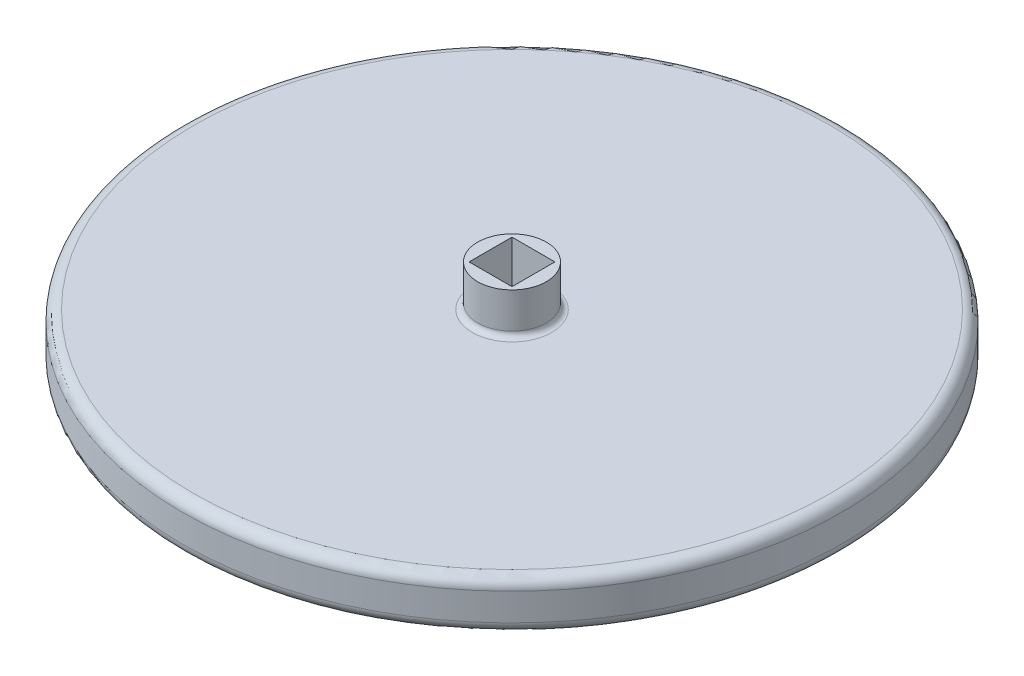
SolidWorks part; units mm, degrees
ref_plane "Front Plane" through (0, 0, 0) normal (0, 0, 1) x (1, 0, 0)
ref_plane "Top Plane" through (0, 0, 0) normal (0, 1, 0) x (1, 0, 0)
ref_plane "Right Plane" through (0, 0, 0) normal (1, 0, 0) x (0, 0, -1)
sketch "Sketch1" plane through (0, 0, 0) normal (0, 1, 0) x (1, 0, 0)
  circle A0 centre (0, 0) radius 76.2
  dimension "D1" = 152.4
extrude "Boss-Extrude1" add sketch "Sketch1" along normal blind 11.43
fillet "Fillet1" radius 2.54 2 edges at (0, 0, 76.2) (0, 11.43, 76.2)
sketch "Sketch3" plane through (0, 11.43, 0) normal (0, 1, 0) x (1, 0, 0)
  circle A0 centre (0, 0) radius 7.9375
  dimension "D1" = 15.875
extrude "Boss-Extrude2" add sketch "Sketch3" along normal blind 9.525 and the other way blind 20.955
fillet "Fillet2" radius 1.27 2 edges at (0, 0, 7.9375) (0, 11.43, 7.9375)
sketch "Sketch2" plane through (0, 11.43, 0) normal (0, 1, 0) x (1, 0, 0)
  line L1 (4.9609, -4.9609) -> (-4.9609, -4.9609)
  line L2 (4.9609, -4.9609) -> (4.9609, 4.9609)
  line L3 (4.9609, 4.9609) -> (-4.9609, 4.9609)
  line L4 (-4.9609, -4.9609) -> (-4.9609, 4.9609)
  line L5 (4.9609, -4.9609) -> (-4.9609, 4.9609) construction
  line L6 (4.9609, 4.9609) -> (-4.9609, -4.9609) construction
  point P0 (0, 0)
  dimension "D1" = 9.9219
  dimension "D2" = 9.9219
extrude "Cut-Extrude1" cut sketch "Sketch2" against normal through all both and the other way through all
